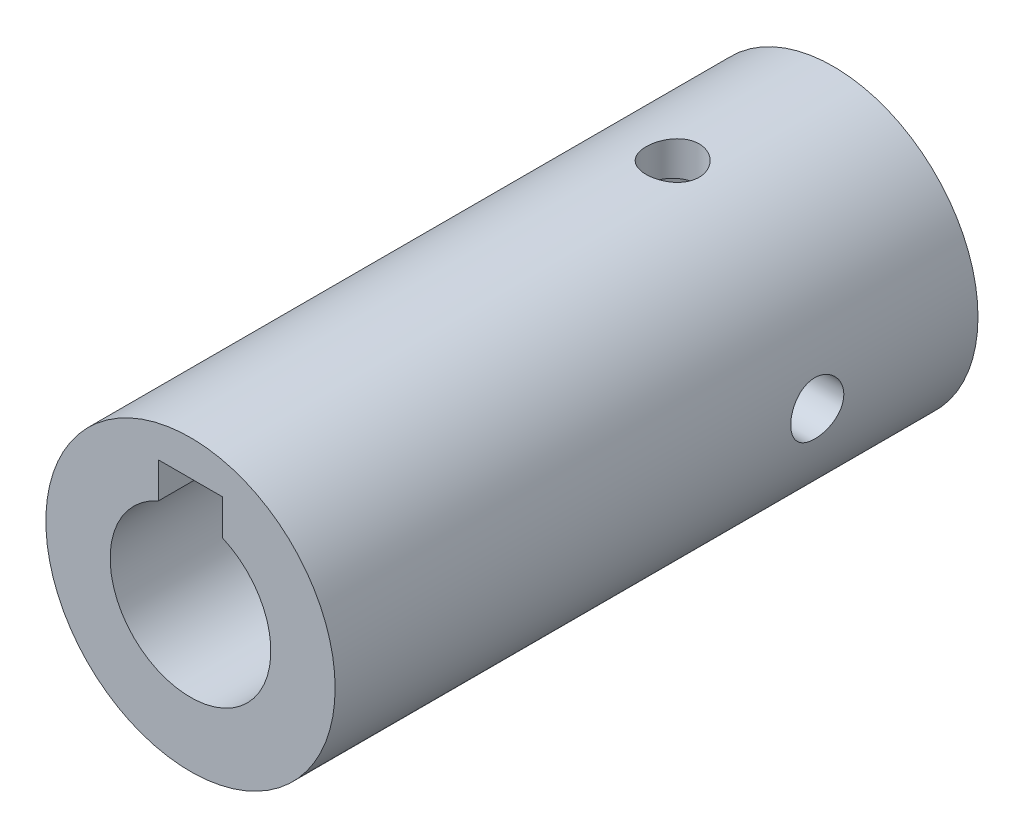
SolidWorks part; units mm, degrees
material "6061 合金"
ref_plane "前视基准面" through (0, 0, 0) normal (0, 0, 1) x (1, 0, 0)
ref_plane "上视基准面" through (0, 0, 0) normal (0, 1, 0) x (1, 0, 0)
ref_plane "右视基准面" through (0, 0, 0) normal (1, 0, 0) x (0, 0, -1)
sketch "草图1" plane through (0, 0, 0) normal (0, 0, 1) x (1, 0, 0)
  circle A0 centre (0, 0) radius 9
  circle A1 centre (0, 0) radius 5
  dimension "D1" = 18
  dimension "D2" = 10
extrude "拉伸1" add sketch "草图1" along normal blind 40
sketch "草图2" plane through (0, 0, 40) normal (0, 0, 1) x (1, 0, 0)
  line L1 (-2, 6.8) -> (2, 6.8)
  line L2 (-2, 6.8) -> (-2, 3.497)
  line L3 (-2, 3.497) -> (2, 3.497)
  line L4 (2, 6.8) -> (2, 3.497)
  line L5 (-2, 6.8) -> (2, 3.497) construction
  line L6 (-2, 3.497) -> (2, 6.8) construction
  circle A0 centre (0, 0) radius 5 construction
  point P0 (0, 5.1485)
  dimension "D2" = 6.8
  dimension "D1" = 4
extrude "拉伸2" cut sketch "草图2" against normal through all
hole_wizard "M4 螺纹孔2" positions "草图4" profile "草图3" tap size "M4" standard "ISO"
sketch "草图4" plane through (0, 0, 0) normal (0, 1, 0) x (1, 0, 0)
  point P1 (0, -10)
  dimension "D1" = 10
sketch "草图3" plane through (0, 0, 10) normal (1, 0, 0) x (0, 0, -1)
  line L0 (0, 0) -> (0, 9)
  line L1 (0, 9) -> (1.65, 9)
  line L2 (1.65, 9) -> (1.65, 0)
  line L5 (1.65, 0) -> (0, 0)
  line L11 (0, -6.35) -> (0, 107.95) construction
  dimension "通孔螺纹孔钻头直径" = 3.3
  dimension "通孔螺纹孔钻头深度" = 9
cosmetic thread "孔螺蚊线1" parameters "D1"=2.2, "D2"=4
pattern_circular "阵列(圆周)1" count 2 every 90 about axis through (0, 0, 40) along (0, 0, -1) of "M4 螺纹孔2"
